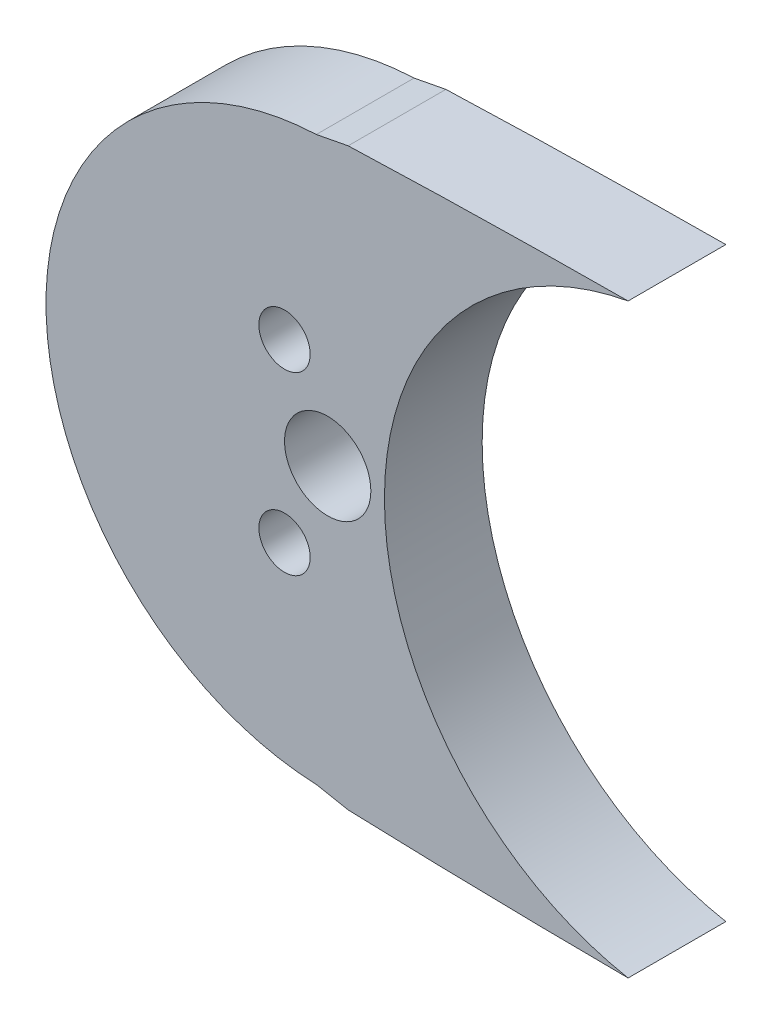
SolidWorks part; units mm, degrees
ref_plane "Front Plane" through (0, 0, 0) normal (0, 0, 1) x (1, 0, 0)
ref_plane "Top Plane" through (0, 0, 0) normal (0, 1, 0) x (1, 0, 0)
ref_plane "Right Plane" through (0, 0, 0) normal (1, 0, 0) x (0, 0, -1)
other "Center of Mass"
curve "Curve2"
  spline degree 3 poles (300, 0.378, 0) (299.8459, 0.3996, 0) (299.2303, 0.4859, 0) (297.8489, 0.6785, 0) (295.556, 0.9968, 0) (292.3657, 1.4334, 0) (288.2979, 1.9834, 0) (283.3772, 2.6357, 0) (277.6343, 3.3815, 0) (271.1045, 4.209, 0) (263.8281, 5.1072, 0) (255.8498, 6.0628, 0) (247.219, 7.0642, 0) (237.9888, 8.0979, 0) (228.216, 9.1511, 0) (217.9611, 10.2107, 0) (207.2872, 11.2632, 0) (196.2601, 12.2937, 0) (184.9478, 13.2887, 0) (173.4201, 14.2316, 0) (161.7479, 15.107, 0) (150.0032, 15.8986, 0) (138.2584, 16.5898, 0) (126.5858, 17.1634, 0) (115.0575, 17.6038, 0) (103.7442, 17.8968, 0) (92.7158, 18.028, 0) (82.0402, 17.9871, 0) (71.7831, 17.7661, 0) (62.0077, 17.3595, 0) (52.7741, 16.7661, 0) (44.1391, 15.9878, 0) (36.1555, 15.0306, 0) (28.872, 13.9026, 0) (22.3327, 12.6157, 0) (16.576, 11.1845, 0) (11.6345, 9.6228, 0) (7.5334, 7.9452, 0) (4.2857, 6.163, 0) (1.8965, 4.2728, 0) (0.3663, 2.2288, 0) (-0.1707, 0, 0) (0.3663, -2.2288, 0) (1.8965, -4.2728, 0) (4.2857, -6.163, 0) (7.5334, -7.9452, 0) (11.6345, -9.6228, 0) (16.576, -11.1845, 0) (22.3327, -12.6157, 0) (28.872, -13.9026, 0) (36.1555, -15.0306, 0) (44.1391, -15.9878, 0) (52.7741, -16.7661, 0) (62.0077, -17.3595, 0) (71.7831, -17.7661, 0) (82.0402, -17.9871, 0) (92.7158, -18.028, 0) (103.7442, -17.8968, 0) (115.0575, -17.6038, 0) (126.5858, -17.1634, 0) (138.2584, -16.5898, 0) (150.0032, -15.8986, 0) (161.7479, -15.107, 0) (173.4201, -14.2316, 0) (184.9478, -13.2887, 0) (196.2601, -12.2937, 0) (207.2872, -11.2632, 0) (217.9611, -10.2107, 0) (228.216, -9.1511, 0) (237.9888, -8.0979, 0) (247.219, -7.0642, 0) (255.8498, -6.0628, 0) (263.8281, -5.1072, 0) (271.1045, -4.209, 0) (277.6343, -3.3815, 0) (283.3772, -2.6357, 0) (288.2979, -1.9834, 0) (292.3657, -1.4334, 0) (295.556, -0.9968, 0) (297.8489, -0.6785, 0) (299.2303, -0.4859, 0) (299.8459, -0.3996, 0) (300, -0.378, 0) knots 0 0 0 0 0.000763 0.003048 0.006841 0.012116 0.018841 0.026973 0.03646 0.047243 0.059254 0.072417 0.086651 0.101866 0.117969 0.134858 0.152428 0.170572 0.189175 0.208122 0.227297 0.24658 0.265853 0.284997 0.303895 0.322433 0.340499 0.357984 0.374788 0.390812 0.405965 0.420162 0.433328 0.445394 0.456301 0.466004 0.474472 0.481696 0.487704 0.492583 0.496544 0.5 0.503456 0.507417 0.512296 0.518304 0.525528 0.533996 0.543699 0.554606 0.566672 0.579838 0.594035 0.609188 0.625212 0.642016 0.659501 0.677567 0.696105 0.715003 0.734147 0.75342 0.772703 0.791878 0.810825 0.829428 0.847572 0.865142 0.882031 0.898134 0.913349 0.927583 0.940746 0.952757 0.96354 0.973027 0.981159 0.987884 0.993159 0.996952 0.999237 1 1 1 1
sketch "Sketch2" plane through (0, 0, 0) normal (0, 0, 1) x (1, 0, 0)
  line L0 (0, 0) -> (300.3287, 0) construction
  line L9 (300, 0.378) -> (300, -0.378)
  line L17 (90, 18.0052) -> (90, -18.0052)
  line L20 (25.2817, 12.903) -> (25.2817, -12.903)
  line L21 (46.6322, 16.1183) -> (46.6322, -16.1183)
  line L22 (68.2099, 17.5933) -> (68.2099, -17.5933)
  line L23 (131.5031, 16.8963) -> (131.5031, -16.8963)
  line L24 (173.2123, 14.1909) -> (173.2123, -14.1909)
  line L25 (215.2898, -10.4186) -> (215.2898, 10.4186)
  line L26 (257.3103, -5.8439) -> (257.3103, 5.8439)
  arc A0 (300, -0.378) -> (300, 0.378) centre (299.947, 0) ccw
  arc A3 (45, 16.0354) -> (45, -16.0354) centre (46.6322, 0) ccw
  arc A5 (67.5, -17.5789) -> (67.5, 17.5789) centre (68.2099, 0) cw
  arc A6 (22.5, 12.5996) -> (22.5, -12.5996) centre (25.2817, 0) ccw
  arc A7 (258, -5.8031) -> (258, 5.8031) centre (257.3103, 0) cw
  arc A8 (216.3287, -10.3667) -> (216.3287, 10.3667) centre (215.2898, 0) cw
  arc A9 (174.3287, -14.147) -> (174.3287, 14.147) centre (173.2123, 0) cw
  arc A11 (132.3287, -16.8761) -> (132.3287, 16.8761) centre (131.5031, 0) cw
  arc A12 (90, -18.0052) -> (90, 18.0052) centre (89.9987, 0) cw
  arc A13 (22.5, 12.5996) -> (22.5, -12.5996) centre (25.2817, 0) cw
  arc A14 (45, 16.0354) -> (45, -16.0354) centre (46.6322, 0) cw
  arc A15 (67.5, 17.5789) -> (67.5, -17.5789) centre (68.2099, 0) cw
  arc A16 (90, -18.0052) -> (90, 18.0052) centre (90, 0) ccw
  arc A17 (132.3287, 16.8761) -> (132.3287, -16.8761) centre (131.5031, 0) cw
  arc A18 (174.3287, 14.147) -> (174.3287, -14.147) centre (173.2123, 0) cw
  arc A19 (216.3287, 10.3667) -> (216.3287, -10.3667) centre (215.2898, 0) cw
  arc A20 (257.9987, 5.8032) -> (257.9987, -5.8032) centre (257.309, 0) cw
  circle A21 centre (25.2817, 0) radius 12.903
  circle A22 centre (257.3103, 0) radius 5.8439
  circle A23 centre (25.2817, 0) radius 2.65
  circle A24 centre (8, 0) radius 2.65
  circle A25 centre (46.6322, 0) radius 2.65
  circle A26 centre (68.2099, 0) radius 2.65
  spline S0 degree 3 poles (1241.5873, 4904.2219) (465.5951, -32.1369) (382.7519, -11.1584) (297.8489, 0.6785) (295.556, 0.9968) (292.3657, 1.4334) (288.2979, 1.9834) (283.3772, 2.6357) (277.6343, 3.3815) (271.1045, 4.209) (263.8281, 5.1072) (255.8498, 6.0628) (247.219, 7.0642) (237.9888, 8.0979) (228.216, 9.1511) (217.9611, 10.2107) (207.2872, 11.2632) (196.2601, 12.2937) (184.9478, 13.2887) (173.4201, 14.2316) (161.7479, 15.107) (150.0032, 15.8986) (138.2584, 16.5898) (126.5858, 17.1634) (115.0575, 17.6038) (103.7442, 17.8968) (92.7158, 18.028) (82.0402, 17.9871) (71.7831, 17.7661) (62.0077, 17.3595) (52.7741, 16.7661) (44.1391, 15.9878) (36.1555, 15.0306) (28.872, 13.9026) (22.3327, 12.6157) (16.576, 11.1845) (11.6345, 9.6228) (7.5334, 7.9452) (4.2857, 6.163) (1.8965, 4.2728) (0.3663, 2.2288) (-0.1707, 0) (0.3663, -2.2288) (1.8965, -4.2728) (4.2857, -6.163) (7.5334, -7.9452) (11.6345, -9.6228) (16.576, -11.1845) (22.3327, -12.6157) (28.872, -13.9026) (36.1555, -15.0306) (44.1391, -15.9878) (52.7741, -16.7661) (62.0077, -17.3595) (71.7831, -17.7661) (82.0402, -17.9871) (92.7158, -18.028) (103.7442, -17.8968) (115.0575, -17.6038) (126.5858, -17.1634) (138.2584, -16.5898) (150.0032, -15.8986) (161.7479, -15.107) (173.4201, -14.2316) (184.9478, -13.2887) (196.2601, -12.2937) (207.2872, -11.2632) (217.9611, -10.2107) (228.216, -9.1511) (237.9888, -8.0979) (247.219, -7.0642) (255.8498, -6.0628) (263.8281, -5.1072) (271.1045, -4.209) (277.6343, -3.3815) (283.3772, -2.6357) (288.2979, -1.9834) (292.3657, -1.4334) (295.556, -0.9968) (297.8489, -0.6785) (382.7525, 11.1585) (465.5962, 32.1372) (1241.6017, -4904.314) knots -0.413585 -0.413585 -0.413585 -0.413585 0.000763 0.003048 0.006841 0.012116 0.018841 0.026973 0.03646 0.047243 0.059254 0.072417 0.086651 0.101866 0.117969 0.134858 0.152428 0.170572 0.189175 0.208122 0.227297 0.24658 0.265853 0.284997 0.303895 0.322433 0.340499 0.357984 0.374788 0.390812 0.405965 0.420162 0.433328 0.445394 0.456301 0.466004 0.474472 0.481696 0.487704 0.492583 0.496544 0.5 0.503456 0.507417 0.512296 0.518304 0.525528 0.533996 0.543699 0.554606 0.566672 0.579838 0.594035 0.609188 0.625212 0.642016 0.659501 0.677567 0.696105 0.715003 0.734147 0.75342 0.772703 0.791878 0.810825 0.829428 0.847572 0.865142 0.882031 0.898134 0.913349 0.927583 0.940746 0.952757 0.96354 0.973027 0.981159 0.987884 0.993159 0.996952 0.999237 1.413588 1.413588 1.413588 1.413588 only from (300, 0.378) to (300, -0.378) construction
  spline S1 degree 3 poles (300, 0.378) (299.8459, 0.3996) (299.2303, 0.4859) (297.8489, 0.6785) (295.556, 0.9968) (292.3657, 1.4334) (288.2979, 1.9834) (283.3772, 2.6357) (277.6343, 3.3815) (271.1045, 4.209) (263.8281, 5.1072) (255.8498, 6.0628) (247.219, 7.0642) (237.9888, 8.0979) (228.216, 9.1511) (217.9611, 10.2107) (207.2872, 11.2632) (196.2601, 12.2937) (184.9478, 13.2887) (173.4201, 14.2316) (161.7479, 15.107) (150.0032, 15.8986) (138.2584, 16.5898) (126.5858, 17.1634) (115.0575, 17.6038) (103.7442, 17.8968) (92.7158, 18.028) (82.0402, 17.9871) (71.7831, 17.7661) (62.0077, 17.3595) (52.7741, 16.7661) (44.1391, 15.9878) (36.1555, 15.0306) (28.872, 13.9026) (22.3327, 12.6157) (16.576, 11.1845) (11.6345, 9.6228) (7.5334, 7.9452) (4.2857, 6.163) (1.8965, 4.2728) (0.3663, 2.2288) (-0.1707, 0) (0.3663, -2.2288) (1.8965, -4.2728) (4.2857, -6.163) (7.5334, -7.9452) (11.6345, -9.6228) (16.576, -11.1845) (22.3327, -12.6157) (28.872, -13.9026) (36.1555, -15.0306) (44.1391, -15.9878) (52.7741, -16.7661) (62.0077, -17.3595) (71.7831, -17.7661) (82.0402, -17.9871) (92.7158, -18.028) (103.7442, -17.8968) (115.0575, -17.6038) (126.5858, -17.1634) (138.2584, -16.5898) (150.0032, -15.8986) (161.7479, -15.107) (173.4201, -14.2316) (184.9478, -13.2887) (196.2601, -12.2937) (207.2872, -11.2632) (217.9611, -10.2107) (228.216, -9.1511) (237.9888, -8.0979) (247.219, -7.0642) (255.8498, -6.0628) (263.8281, -5.1072) (271.1045, -4.209) (277.6343, -3.3815) (283.3772, -2.6357) (288.2979, -1.9834) (292.3657, -1.4334) (295.556, -0.9968) (297.8489, -0.6785) (299.2303, -0.4859) (299.8459, -0.3996) (300, -0.378) knots 0 0 0 0 0.000763 0.003048 0.006841 0.012116 0.018841 0.026973 0.03646 0.047243 0.059254 0.072417 0.086651 0.101866 0.117969 0.134858 0.152428 0.170572 0.189175 0.208122 0.227297 0.24658 0.265853 0.284997 0.303895 0.322433 0.340499 0.357984 0.374788 0.390812 0.405965 0.420162 0.433328 0.445394 0.456301 0.466004 0.474472 0.481696 0.487704 0.492583 0.496544 0.5 0.503456 0.507417 0.512296 0.518304 0.525528 0.533996 0.543699 0.554606 0.566672 0.579838 0.594035 0.609188 0.625212 0.642016 0.659501 0.677567 0.696105 0.715003 0.734147 0.75342 0.772703 0.791878 0.810825 0.829428 0.847572 0.865142 0.882031 0.898134 0.913349 0.927583 0.940746 0.952757 0.96354 0.973027 0.981159 0.987884 0.993159 0.996952 0.999237 1 1 1 1
  point P47 (215.2898, 0)
  point P58 (257.3103, 0)
  point P61 (12.3787, 0)
  point P62 (62.7505, 0)
  dimension "D11" = 5.3
  dimension "D14" = 5.3
  dimension "D12" = 5.3
  dimension "D15" = 5.3
  dimension "D1" = 300.3287
  dimension "D2" = 89.9987
  dimension "D3" = 68.2099
  dimension "D4" = 46.6322
  dimension "D5" = 25.2817
  dimension "D6" = 168.8256
  dimension "D7" = 127.1164
  dimension "D8" = 85.0389
  dimension "D9" = 43.0184
  dimension "D10" = 50.3718
  dimension "D13" = 8
extrude "Boss-Extrude5" add sketch "Sketch2" along normal blind 6 from offset 4.25 contours A14 L0 A26 L22 A15 A5 | A5 L0 A14 | L0 A5 A14 | L0 A14 A5 A15 L22 A26 | A26 L0 A12 A15 L22 | L0 A26 L22 A15 A12 | A12 S1 A15 | A15 S1 A12
sketch "Sketch3" plane through (0, 0, 10.25) normal (0, 0, 1) x (1, 0, 0)
  line L0 (67.5121, 17.2792) -> (69.4665, 17.6542)
  line L1 (67.5121, -17.2792) -> (69.4665, -17.6542)
  arc A0 (67.5121, 17.2792) -> (67.5121, -17.2792) centre (68.2099, 0) ccw
  arc A1 (90, 18.3052) -> (90, -18.3052) centre (89.9987, 0) ccw
  arc A2 (67.5, 17.5789) -> (67.5, -17.5789) centre (68.2099, 0) ccw
  arc A3 (90, 18.0052) -> (90, -18.0052) centre (89.9987, 0) ccw
  arc A4 (67.5, 17.5789) -> (67.5, -17.5789) centre (68.2099, 0) ccw
  arc A5 (90, 18.0052) -> (90, -18.0052) centre (89.9987, 0) ccw
  spline S2 degree 3 poles (-238.8002, 2917.1978) (-404.6037, 171.2192) (-165.8113, -12.6473) (408.3425, -25.0171) (745.002, 249.2503) (674.9084, -2853.1343) knots -0.556272 -0.556272 -0.556272 -0.556272 0.625212 0.642016 2.260096 2.260096 2.260096 2.260096 only from (67.5, -17.5789) to (90, -18.0052)
  spline S3 degree 3 poles (674.9068, 2853.2067) (745.0072, -249.2545) (408.345, 25.0172) (-165.809, 12.6474) (-404.5992, -171.2158) (-238.805, -2917.119) knots -1.260108 -1.260108 -1.260108 -1.260108 0.357984 0.374788 1.556261 1.556261 1.556261 1.556261 only from (90, 18.0052) to (67.5, 17.5789)
  spline S4 degree 3 poles (67.5, -17.5789) (68.8749, -17.6344) (73.6741, -17.8069) (81.1746, -17.9685) (87.3004, -18.0054) (90, -18.0052) knots 0.618464 0.618464 0.618464 0.618464 0.625212 0.642016 0.655255 0.655255 0.655255 0.655255
  spline S5 degree 3 poles (90, 18.0052) (87.3004, 18.0054) (81.1746, 17.9685) (73.6741, 17.8069) (68.8749, 17.6344) (67.5, 17.5789) knots 0.344745 0.344745 0.344745 0.344745 0.357984 0.374788 0.381536 0.381536 0.381536 0.381536
  arc M5 (67.5, 17.5789) -> (67.5, -17.5789) centre (68.2099, 0) ccw
  spline M6 degree 3 poles (300, 0.378) (299.8459, 0.3996) (299.2303, 0.4859) (297.8489, 0.6785) (295.556, 0.9968) (292.3657, 1.4334) (288.2979, 1.9834) (283.3772, 2.6357) (277.6343, 3.3815) (271.1045, 4.209) (263.8281, 5.1072) (255.8498, 6.0628) (247.219, 7.0642) (237.9888, 8.0979) (228.216, 9.1511) (217.9611, 10.2107) (207.2872, 11.2632) (196.2601, 12.2937) (184.9478, 13.2887) (173.4201, 14.2316) (161.7479, 15.107) (150.0032, 15.8986) (138.2584, 16.5898) (126.5858, 17.1634) (115.0575, 17.6038) (103.7442, 17.8968) (92.7158, 18.028) (82.0402, 17.9871) (71.7831, 17.7661) (62.0077, 17.3595) (52.7741, 16.7661) (44.1391, 15.9878) (36.1555, 15.0306) (28.872, 13.9026) (22.3327, 12.6157) (16.576, 11.1845) (11.6345, 9.6228) (7.5334, 7.9452) (4.2857, 6.163) (1.8965, 4.2728) (0.3663, 2.2288) (-0.1707, 0) (0.3663, -2.2288) (1.8965, -4.2728) (4.2857, -6.163) (7.5334, -7.9452) (11.6345, -9.6228) (16.576, -11.1845) (22.3327, -12.6157) (28.872, -13.9026) (36.1555, -15.0306) (44.1391, -15.9878) (52.7741, -16.7661) (62.0077, -17.3595) (71.7831, -17.7661) (82.0402, -17.9871) (92.7158, -18.028) (103.7442, -17.8968) (115.0575, -17.6038) (126.5858, -17.1634) (138.2584, -16.5898) (150.0032, -15.8986) (161.7479, -15.107) (173.4201, -14.2316) (184.9478, -13.2887) (196.2601, -12.2937) (207.2872, -11.2632) (217.9611, -10.2107) (228.216, -9.1511) (237.9888, -8.0979) (247.219, -7.0642) (255.8498, -6.0628) (263.8281, -5.1072) (271.1045, -4.209) (277.6343, -3.3815) (283.3772, -2.6357) (288.2979, -1.9834) (292.3657, -1.4334) (295.556, -0.9968) (297.8489, -0.6785) (299.2303, -0.4859) (299.8459, -0.3996) (300, -0.378) knots 0 0 0 0 0.000763 0.003048 0.006841 0.012116 0.018841 0.026973 0.03646 0.047243 0.059254 0.072417 0.086651 0.101866 0.117969 0.134858 0.152428 0.170572 0.189175 0.208122 0.227297 0.24658 0.265853 0.284997 0.303895 0.322433 0.340499 0.357984 0.374788 0.390812 0.405965 0.420162 0.433328 0.445394 0.456301 0.466004 0.474472 0.481696 0.487704 0.492583 0.496544 0.5 0.503456 0.507417 0.512296 0.518304 0.525528 0.533996 0.543699 0.554606 0.566672 0.579838 0.594035 0.609188 0.625212 0.642016 0.659501 0.677567 0.696105 0.715003 0.734147 0.75342 0.772703 0.791878 0.810825 0.829428 0.847572 0.865142 0.882031 0.898134 0.913349 0.927583 0.940746 0.952757 0.96354 0.973027 0.981159 0.987884 0.993159 0.996952 0.999237 1 1 1 1 only from (67.5, -17.5789) to (90, -18.0052)
  arc M7 (90, -18.0052) -> (90, 18.0052) centre (89.9987, 0) cw
  spline M8 degree 3 poles (300, 0.378) (299.8459, 0.3996) (299.2303, 0.4859) (297.8489, 0.6785) (295.556, 0.9968) (292.3657, 1.4334) (288.2979, 1.9834) (283.3772, 2.6357) (277.6343, 3.3815) (271.1045, 4.209) (263.8281, 5.1072) (255.8498, 6.0628) (247.219, 7.0642) (237.9888, 8.0979) (228.216, 9.1511) (217.9611, 10.2107) (207.2872, 11.2632) (196.2601, 12.2937) (184.9478, 13.2887) (173.4201, 14.2316) (161.7479, 15.107) (150.0032, 15.8986) (138.2584, 16.5898) (126.5858, 17.1634) (115.0575, 17.6038) (103.7442, 17.8968) (92.7158, 18.028) (82.0402, 17.9871) (71.7831, 17.7661) (62.0077, 17.3595) (52.7741, 16.7661) (44.1391, 15.9878) (36.1555, 15.0306) (28.872, 13.9026) (22.3327, 12.6157) (16.576, 11.1845) (11.6345, 9.6228) (7.5334, 7.9452) (4.2857, 6.163) (1.8965, 4.2728) (0.3663, 2.2288) (-0.1707, 0) (0.3663, -2.2288) (1.8965, -4.2728) (4.2857, -6.163) (7.5334, -7.9452) (11.6345, -9.6228) (16.576, -11.1845) (22.3327, -12.6157) (28.872, -13.9026) (36.1555, -15.0306) (44.1391, -15.9878) (52.7741, -16.7661) (62.0077, -17.3595) (71.7831, -17.7661) (82.0402, -17.9871) (92.7158, -18.028) (103.7442, -17.8968) (115.0575, -17.6038) (126.5858, -17.1634) (138.2584, -16.5898) (150.0032, -15.8986) (161.7479, -15.107) (173.4201, -14.2316) (184.9478, -13.2887) (196.2601, -12.2937) (207.2872, -11.2632) (217.9611, -10.2107) (228.216, -9.1511) (237.9888, -8.0979) (247.219, -7.0642) (255.8498, -6.0628) (263.8281, -5.1072) (271.1045, -4.209) (277.6343, -3.3815) (283.3772, -2.6357) (288.2979, -1.9834) (292.3657, -1.4334) (295.556, -0.9968) (297.8489, -0.6785) (299.2303, -0.4859) (299.8459, -0.3996) (300, -0.378) knots 0 0 0 0 0.000763 0.003048 0.006841 0.012116 0.018841 0.026973 0.03646 0.047243 0.059254 0.072417 0.086651 0.101866 0.117969 0.134858 0.152428 0.170572 0.189175 0.208122 0.227297 0.24658 0.265853 0.284997 0.303895 0.322433 0.340499 0.357984 0.374788 0.390812 0.405965 0.420162 0.433328 0.445394 0.456301 0.466004 0.474472 0.481696 0.487704 0.492583 0.496544 0.5 0.503456 0.507417 0.512296 0.518304 0.525528 0.533996 0.543699 0.554606 0.566672 0.579838 0.594035 0.609188 0.625212 0.642016 0.659501 0.677567 0.696105 0.715003 0.734147 0.75342 0.772703 0.791878 0.810825 0.829428 0.847572 0.865142 0.882031 0.898134 0.913349 0.927583 0.940746 0.952757 0.96354 0.973027 0.981159 0.987884 0.993159 0.996952 0.999237 1 1 1 1 only from (90, 18.0052) to (67.5, 17.5789)
  dimension "D1" = 0
  dimension "D2" = 0.3
  dimension "D3" = 0.3
extrude "Cut-Extrude2" cut sketch "Sketch3" against normal through all contours A1 M8 M6 M7 | A0 L0 L1 M8 M5 M6
other "Center of Mass Reference Point1"
sketch "Sketch4" plane through (0, 0, 10.25) normal (0, 0, 1) x (1, 0, 0)
  line L0 (0, 0) -> (110.0921, 0) construction
  line L1 (65.5599, 5.4) -> (65.5599, -5.4) construction
  circle A1 centre (65.5599, 5.4) radius 1.575
  circle A2 centre (65.5599, -5.4) radius 1.575
  point P6 (65.5599, 0)
  dimension "D2" = 3.15
  dimension "D3" = 3.15
  dimension "D1" = 10.8
extrude "Cut-Extrude3" cut sketch "Sketch4" against normal blind 10
